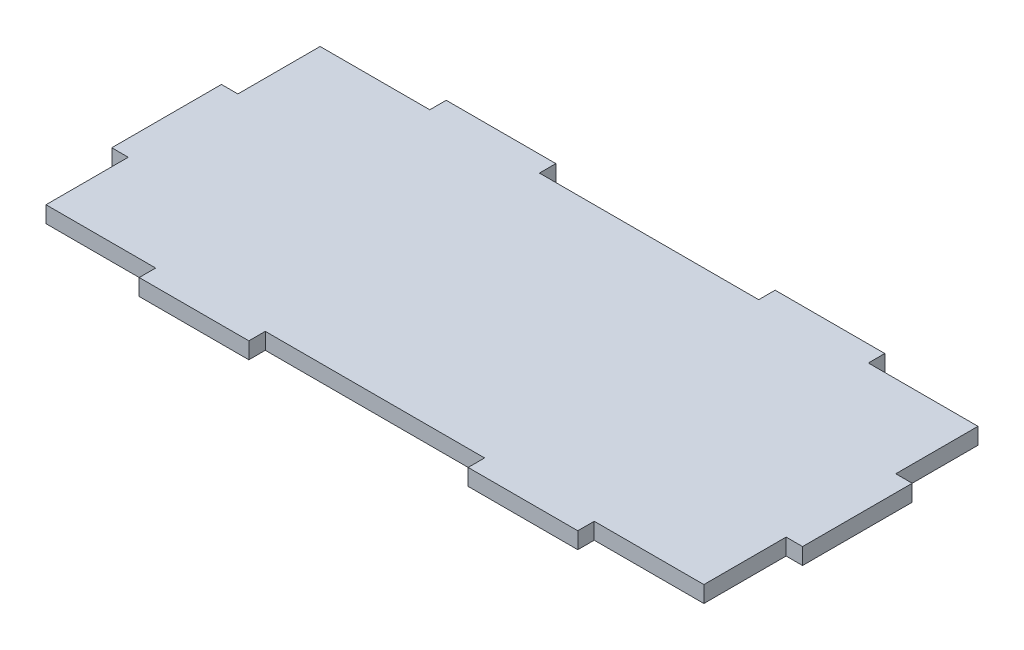
SolidWorks part; units mm, degrees
ref_plane "Front Plane" through (0, 0, 0) normal (0, 0, 1) x (1, 0, 0)
ref_plane "Top Plane" through (0, 0, 0) normal (0, 1, 0) x (1, 0, 0)
ref_plane "Right Plane" through (0, 0, 0) normal (1, 0, 0) x (0, 0, -1)
sketch "Sketch2" plane through (0, 0, 0) normal (0, 1, 0) x (1, 0, 0)
  line L0 (0, 50) -> (0, 35) construction
  line L1 (0, 0) -> (20, 0)
  line L2 (0, 0) -> (0, 15)
  line L3 (0, 50) -> (20, 50)
  line L4 (120, 0) -> (120, 15)
  line L5 (0, 50) -> (20, 50) construction
  line L6 (0, 15) -> (-3, 15)
  line L8 (0, 35) -> (-3, 35)
  line L9 (-3, 15) -> (-3, 35)
  line L10 (40, 50) -> (80, 50)
  line L11 (40, 50) -> (80, 50) construction
  line L12 (60, 50) -> (40, 50) construction
  line L13 (100, 0) -> (120, 0)
  line L14 (20, 53) -> (40, 53)
  line L15 (20, 53) -> (20, 50)
  line L17 (40, 53) -> (40, 50)
  line L18 (40, 0) -> (80, 0)
  line L19 (80, -3) -> (80, 0)
  line L21 (40, -3) -> (40, 0)
  line L23 (20, -3) -> (20, 0)
  line L24 (20, -3) -> (40, -3)
  line L25 (0, 15) -> (0, 0) construction
  line L26 (0, 35) -> (0, 50)
  line L27 (20, 50) -> (0, 50) construction
  line L28 (100, -3) -> (80, -3)
  line L29 (100, -3) -> (100, 0)
  line L30 (120, 15) -> (123, 15)
  line L31 (123, 15) -> (123, 35)
  line L32 (120, 35) -> (123, 35)
  line L33 (100, 53) -> (100, 50)
  line L34 (80, 53) -> (80, 50)
  line L35 (100, 53) -> (80, 53)
  line L36 (100, 50) -> (120, 50)
  line L37 (100, 50) -> (120, 50) construction
  line L38 (120, 35) -> (120, 50)
  point P4 (0, 25)
  point P11 (30, 50)
  dimension "D1" = 120
  dimension "D2" = 50
  dimension "2" = 20
  dimension "D5" = 20
extrude "Boss-Extrude1" add sketch "Sketch2" along normal blind 3
